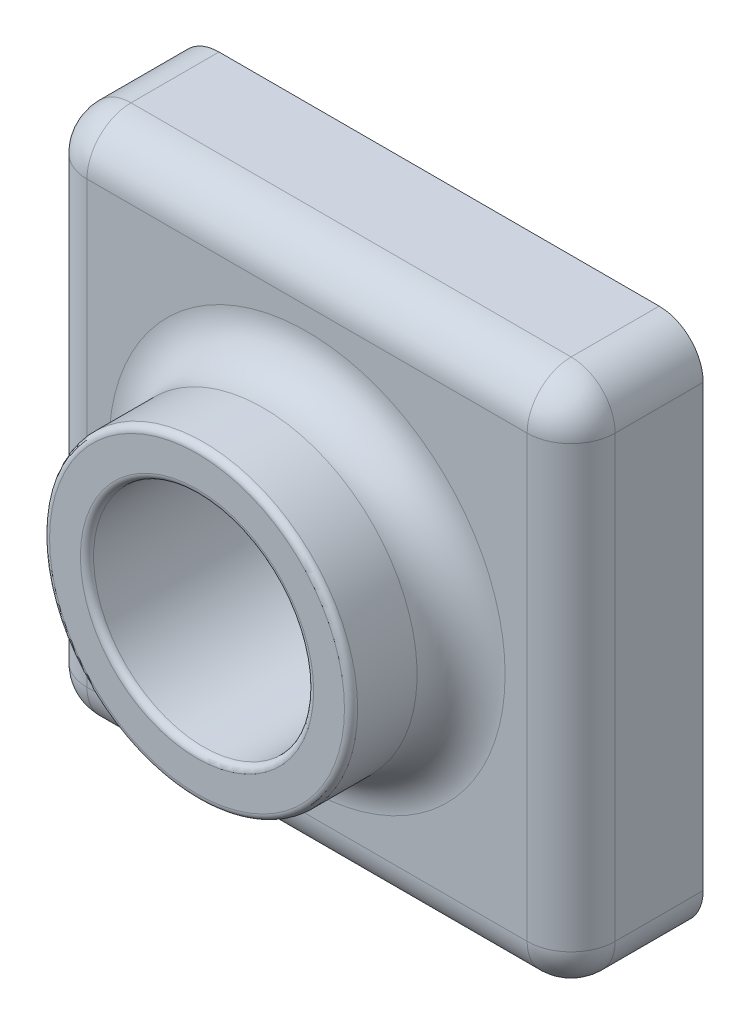
SolidWorks part; units mm, degrees
ref_plane "Front Plane" through (0, 0, 0) normal (0, 0, 1) x (1, 0, 0)
ref_plane "Top Plane" through (0, 0, 0) normal (0, 1, 0) x (1, 0, 0)
ref_plane "Right Plane" through (0, 0, 0) normal (1, 0, 0) x (0, 0, -1)
sketch "Sketch4" plane through (0, 0, 0) normal (0, 0, 1) x (1, 0, 0)
  line L1 (0, 0) -> (120, 0)
  line L2 (0, 0) -> (0, 120)
  line L3 (0, 120) -> (120, 120)
  line L4 (120, 0) -> (120, 120)
  dimension "D1" = 120
  dimension "D2" = 120
extrude "Boss-Extrude1" add sketch "Sketch4" along normal blind 30
sketch "Sketch6" plane through (0, 0, 30) normal (0, 0, 1) x (1, 0, 0)
  line L0 (120, 120) -> (0, 120) construction
  line L1 (120, 0) -> (120, 120) construction
  circle A0 centre (60, 60) radius 35
  dimension "D1" = 70
  dimension "D2" = 60
  dimension "D3" = 60
extrude "Boss-Extrude2" add sketch "Sketch6" along normal blind 25
sketch "Sketch8" plane through (0, 0, 55) normal (0, 0, 1) x (1, 0, 0)
  circle A0 centre (60, 60) radius 25
  dimension "D1" = 50
extrude "Cut-Extrude1" cut sketch "Sketch8" against normal through all
fillet "Fillet1" radius 10 9 edges at (60, 120, 30) (120, 60, 30) (60, 0, 30) (0, 60, 30) (95, 60, 30) (120, 0, 15) (0, 0, 15) (0, 120, 15) (120, 120, 15)
fillet "Fillet2" radius 1.5 2 edges at (95, 60, 55) (85, 60, 55)
shell "Shell1" thickness 2
